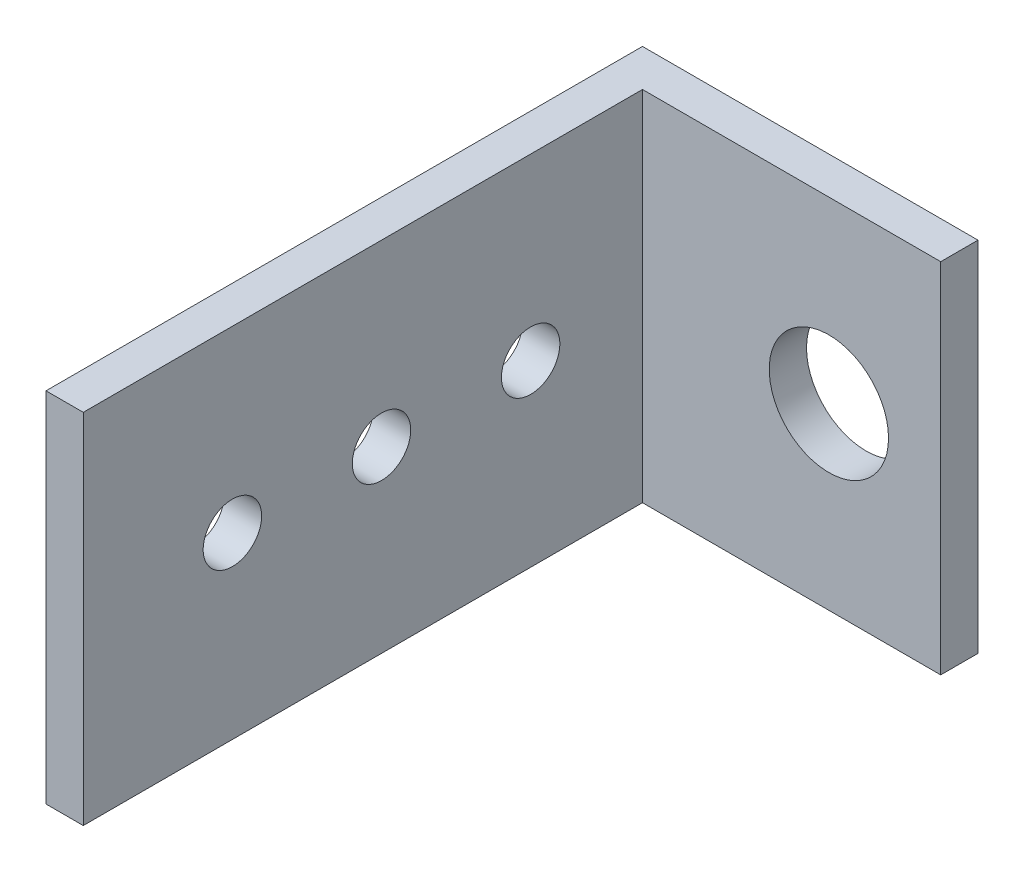
SolidWorks part; units mm, degrees
material "6061-T6 (SS)"
ref_plane "Front Plane" through (0, 0, 0) normal (0, 0, 1) x (1, 0, 0)
ref_plane "Top Plane" through (0, 0, 0) normal (0, 1, 0) x (1, 0, 0)
ref_plane "Right Plane" through (0, 0, 0) normal (1, 0, 0) x (0, 0, -1)
sketch "Sketch1" plane through (0, 0, 0) normal (0, 1, 0) x (1, 0, 0)
  line L1 (0, 0) -> (3.175, 0)
  line L2 (0, 0) -> (0, 50.8)
  line L3 (0, 50.8) -> (3.175, 50.8)
  line L4 (3.175, 0) -> (3.175, 50.8)
  line L5 (0, 50.8) -> (28.575, 50.8)
  line L6 (0, 50.8) -> (0, 47.625)
  line L7 (0, 47.625) -> (28.575, 47.625)
  line L8 (28.575, 50.8) -> (28.575, 47.625)
  dimension "D1" = 28.575
  dimension "D2" = 50.8
  dimension "D3" = 3.175
  dimension "D4" = 3.175
extrude "Boss-Extrude1" add sketch "Sketch1" along normal blind 30.48 contours L7 L2 L1 L4 | L8 L5 L4 L7 | L2 L7 L4 L3
sketch "Sketch2" plane through (0, 0, -47.625) normal (0, 0, 1) x (1, 0, 0)
  line L0 (28.575, 30.48) -> (28.575, 0) construction
  circle A0 centre (19.05, 15.24) radius 5.08
  point P4 (28.575, 15.24)
  dimension "D1" = 10.16
  dimension "D2" = 9.525
extrude "Cut-Extrude1" cut sketch "Sketch2" against normal blind 32.766
sketch "Sketch3" plane through (3.175, 0, 0) normal (1, 0, 0) x (0, 0, -1)
  line L0 (0, 30.48) -> (0, 0) construction
  circle A0 centre (12.7, 15.24) radius 2.4892
  circle A1 centre (25.4, 15.24) radius 2.4892
  circle A2 centre (38.1, 15.24) radius 2.4892
  point P5 (0, 15.24)
  point P9 (0, 0)
  dimension "D1" = 4.9784
  dimension "D3" = 12.7
  dimension "D4" = 12.7
  dimension "D2" = 12.7
extrude "Cut-Extrude2" cut sketch "Sketch3" against normal blind 32.766
